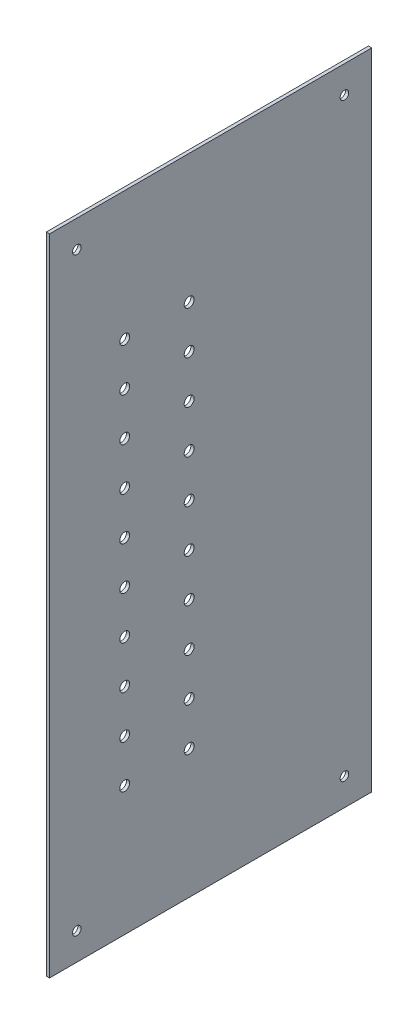
SolidWorks part; units mm, degrees
material "5052-H32"
ref_plane "Front Plane" through (0, 0, 0) normal (1, 0, 0) x (0, 1, 0)
ref_plane "Top Plane" through (0, 0, 0) normal (0, 0, 1) x (0, 1, 0)
ref_plane "Right Plane" through (0, 0, 0) normal (0, 1, 0) x (-1, 0, 0)
sketch "Sketch1" plane through (0, 0, 0) normal (1, 0, 0) x (0, 1, 0)
  line L1 (-150, -75) -> (150, -75)
  line L2 (-150, -75) -> (-150, 75)
  line L3 (-150, 75) -> (150, 75)
  line L4 (150, -75) -> (150, 75)
  line L5 (-150, -75) -> (150, 75) construction
  line L6 (-150, 75) -> (150, -75) construction
  point P0 (0, 0)
extrude "Boss-Extrude1" add sketch "Sketch1" along normal blind 1.52
hole_wizard "Ø4.0 (4) Diameter Hole1" positions "Sketch2" profile "Sketch3" hole size "Ø4.0" standard "ISO" end condition through all
sketch "Sketch2" plane through (1.52, 0, 0) normal (1, 0, 0) x (0, 1, 0)
  line L0 (-150, 75) -> (-150, -75) construction
  line L1 (150, 75) -> (-150, 75) construction
  point P0 (-137.3, 62.3)
  dimension "D1" = 12.7
  dimension "D2" = 12.7
sketch "Sketch3" plane through (1.52, -137.3, 62.3) normal (0, 1, 0) x (0, 0, -1)
  line L0 (0, 0) -> (0, 1.52)
  line L1 (0, 1.52) -> (2, 1.52)
  line L2 (2, 1.52) -> (2, 0)
  line L5 (2, 0) -> (0, 0)
  line L11 (0, -6.35) -> (0, 107.95) construction
  dimension "Thru Hole Dia." = 4
  dimension "Thru Hole Depth" = 1.52
mirror "Mirror1" about plane through (0, 0, 0) normal (0, 1, 0) of "Ø4.0 (4) Diameter Hole1" second plane through (0, 0, 0) second plane normal (0, 0, 1)
hole_wizard "Ø4.6 (4.6) Diameter Hole1" positions "Sketch4" profile "Sketch5" hole size "Ø4.6" standard "ISO" end condition through all
sketch "Sketch4" plane through (1.52, 0, 0) normal (1, 0, 0) x (0, 1, 0)
  point P0 (-90, 40)
  point P2 (-70, 40)
  point P4 (-50, 40)
  point P6 (-30, 40)
  point P8 (-10, 40)
  point P10 (10, 40)
  point P12 (30, 40)
  point P14 (50, 40)
  point P16 (70, 40)
  point P18 (90, 40)
  dimension "D1" = 20
  dimension "D2" = 20
  dimension "D3" = 20
  dimension "D4" = 20
  dimension "D5" = 20
  dimension "D6" = 20
  dimension "D7" = 20
  dimension "D8" = 20
  dimension "D9" = 20
  dimension "D10" = 10
  dimension "D11" = 40
sketch "Sketch5" plane through (1.52, -90, 40) normal (0, 1, 0) x (0, 0, -1)
  line L0 (0, 0) -> (0, 1.52)
  line L1 (0, 1.52) -> (2.3, 1.52)
  line L2 (2.3, 1.52) -> (2.3, 0)
  line L5 (2.3, 0) -> (0, 0)
  line L11 (0, -6.35) -> (0, 107.95) construction
  dimension "Thru Hole Dia." = 4.6
  dimension "Thru Hole Depth" = 1.52
hole_wizard "Ø4.6 (4.6) Diameter Hole2" positions "Sketch6" profile "Sketch7" hole size "Ø4.6" standard "ISO" end condition through all
sketch "Sketch6" plane through (1.52, 0, 0) normal (1, 0, 0) x (0, 1, 0)
  circle A2 centre (-90, 40) radius 2.3 construction
  point P0 (-90, 10)
  point P2 (-70, 10)
  point P4 (-50, 10)
  point P6 (-30, 10)
  point P8 (-10, 10)
  point P10 (10, 10)
  point P12 (30, 10)
  point P14 (50, 10)
  point P16 (70, 10)
  point P18 (90, 10)
  dimension "D1" = 30
  dimension "D2" = 20
  dimension "D3" = 20
  dimension "D4" = 20
  dimension "D5" = 20
  dimension "D6" = 20
  dimension "D7" = 20
  dimension "D8" = 20
  dimension "D9" = 20
  dimension "D10" = 20
  dimension "D11" = 10
sketch "Sketch7" plane through (1.52, -90, 10) normal (0, 1, 0) x (0, 0, -1)
  line L0 (0, 0) -> (0, 1.52)
  line L1 (0, 1.52) -> (2.3, 1.52)
  line L2 (2.3, 1.52) -> (2.3, 0)
  line L5 (2.3, 0) -> (0, 0)
  line L11 (0, -6.35) -> (0, 107.95) construction
  dimension "Thru Hole Dia." = 4.6
  dimension "Thru Hole Depth" = 1.52
